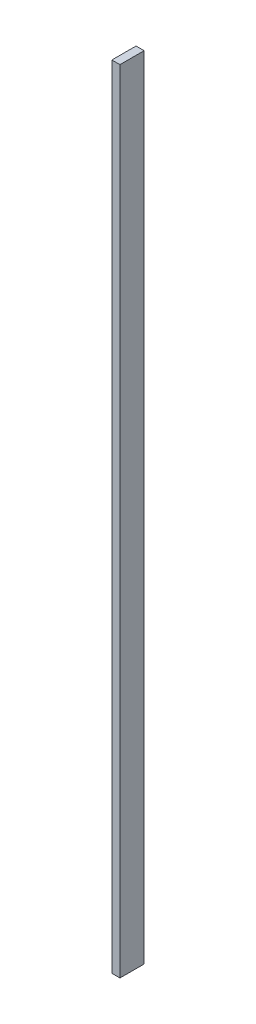
SolidWorks part; units mm, degrees
ref_plane "Front Plane" through (0, 0, 0) normal (0, 0, 1) x (1, 0, 0)
ref_plane "Top Plane" through (0, 0, 0) normal (0, 1, 0) x (1, 0, 0)
ref_plane "Right Plane" through (0, 0, 0) normal (1, 0, 0) x (0, 0, -1)
sketch "Sketch1" plane through (0, 0, 0) normal (1, 0, 0) x (0, 0, -1)
  line L1 (19.05, 622.3) -> (-19.05, 622.3)
  line L2 (19.05, 622.3) -> (19.05, -622.3)
  line L3 (19.05, -622.3) -> (-19.05, -622.3)
  line L4 (-19.05, 622.3) -> (-19.05, -622.3)
  line L5 (19.05, 622.3) -> (-19.05, -622.3) construction
  line L6 (19.05, -622.3) -> (-19.05, 622.3) construction
  point P0 (0, 0)
  dimension "D1" = 1244.6
  dimension "D2" = 38.1
extrude "Boss-Extrude1" add sketch "Sketch1" along normal mid plane 12.7
